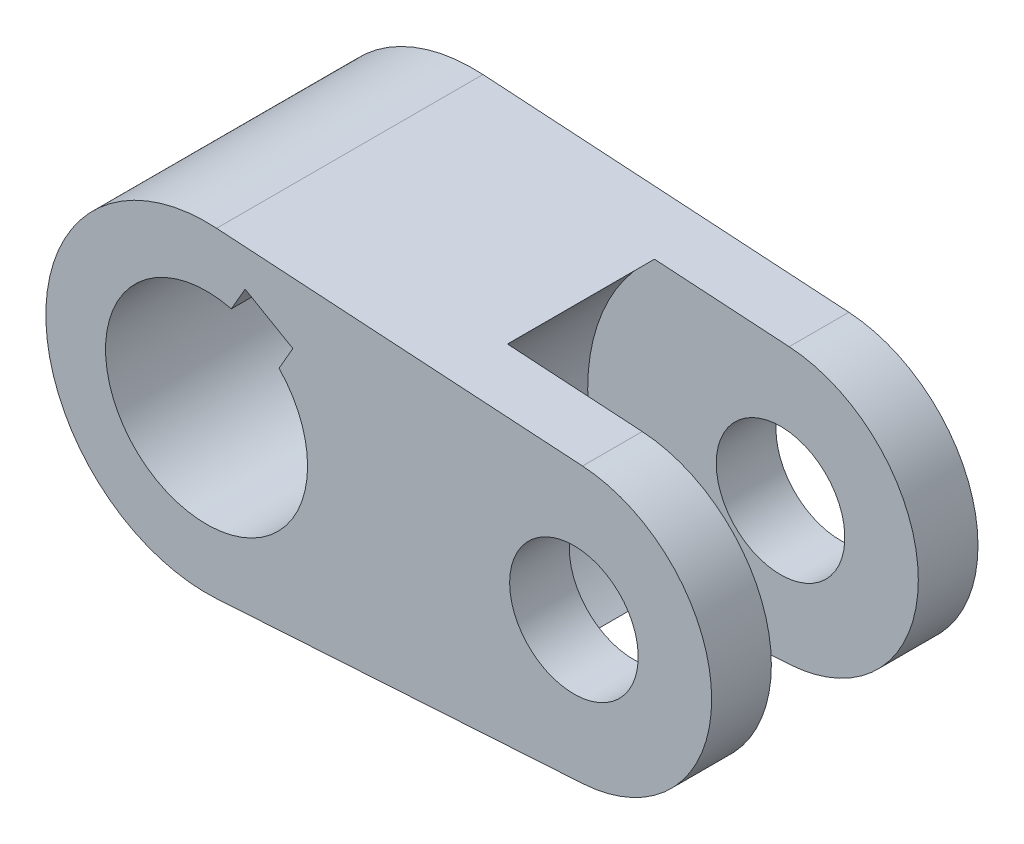
SolidWorks part; units mm, degrees
ref_plane "Спереди" through (0, 0, 0) normal (0, 0, 1) x (1, 0, 0)
ref_plane "Сверху" through (0, 0, 0) normal (0, 1, 0) x (1, 0, 0)
ref_plane "Справа" through (0, 0, 0) normal (1, 0, 0) x (0, 0, -1)
sketch "Эскиз1" plane through (0, 0, 0) normal (0, 0, 1) x (1, 0, 0)
  line L0 (0, 0) -> (40, 0) construction
  line L1 (40.9375, 14.9707) -> (1.0938, 17.4658)
  line L2 (40.9375, -14.9707) -> (1.0938, -17.4658)
  line L3 (0, 0) -> (6.8, 11.7779) construction
  line L4 (2.6934, 10.6652) -> (4.2019, 13.2779)
  line L5 (4.2019, 13.2779) -> (9.3981, 10.2779)
  line L6 (9.3981, 10.2779) -> (7.8896, 7.6652)
  arc A0 (1.0938, 17.4658) -> (1.0938, -17.4658) centre (0, 0) ccw
  arc A1 (40.9375, -14.9707) -> (40.9375, 14.9707) centre (40, 0) ccw
  arc A2 (2.6934, 10.6652) -> (7.8896, 7.6652) centre (0, 0) ccw
  circle A3 centre (40, 0) radius 7
  point P1 (0, 0)
  point P2 (0, 0)
  point P12 (0, 0)
  point P15 (6.8, 11.7779)
  point P16 (0, 0)
  dimension "D1" = 17.5
  dimension "D2" = 15
  dimension "D5" = 22
  dimension "D8" = 14
  dimension "D3" = 40
  dimension "D4" = 24.6
  dimension "D6" = 6
  dimension "D7" = 60
extrude "Бобышка-Вытянуть1" add sketch "Эскиз1" along normal mid plane 29
sketch "Эскиз3" plane through (0, 0, 0) normal (0, 0, 1) x (1, 0, 0)
  circle A0 centre (40, 0) radius 21
  dimension "D1" = 42
extrude "Вырез-Вытянуть1" cut sketch "Эскиз3" against normal mid plane 16
